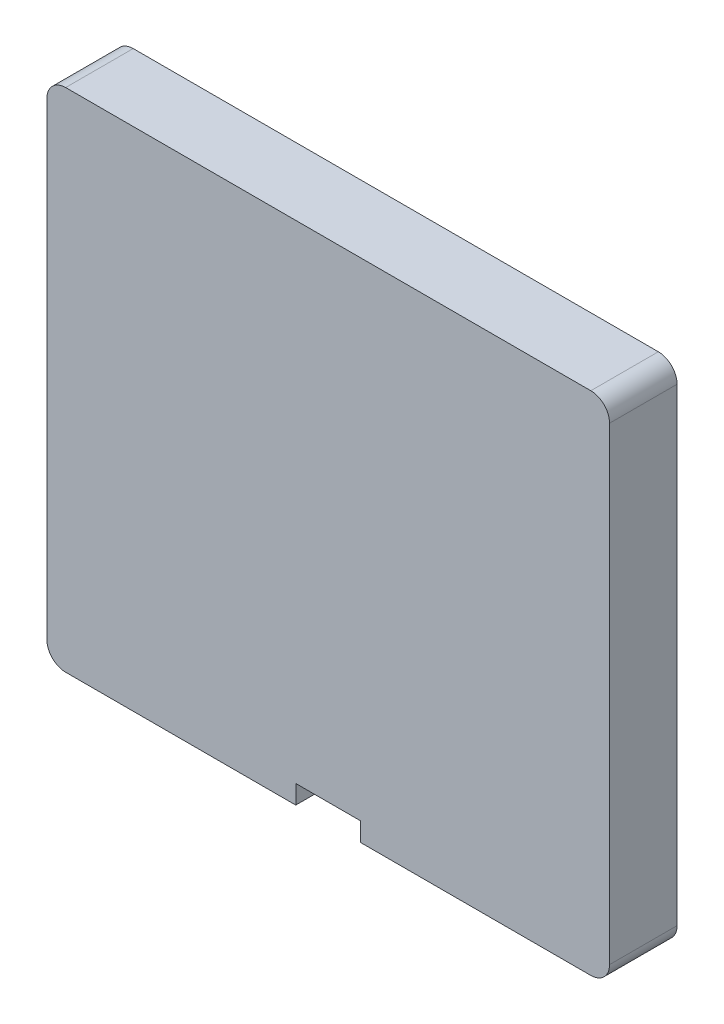
SolidWorks part; units mm, degrees
ref_plane "前视基准面" through (0, 0, 0) normal (0, 0, 1) x (1, 0, 0)
ref_plane "上视基准面" through (0, 0, 0) normal (0, 1, 0) x (1, 0, 0)
ref_plane "右视基准面" through (0, 0, 0) normal (1, 0, 0) x (0, 0, -1)
sketch "草图1" plane through (0, 0, 0) normal (0, 0, 1) x (1, 0, 0)
  line L0 (0, -62.5) -> (0, -47.6331) construction
  line L1 (-70, -67.5) -> (-8.6603, -67.5)
  line L2 (-75, -62.5) -> (-75, 62.5)
  line L3 (-70, 67.5) -> (70, 67.5)
  line L4 (75, -62.5) -> (75, 62.5)
  line L5 (-75, -67.5) -> (75, 67.5) construction
  line L6 (-75, 67.5) -> (75, -67.5) construction
  line L8 (8.6603, -67.5) -> (8.6603, -62.5)
  line L9 (8.6603, -62.5) -> (-8.6603, -62.5)
  line L11 (-8.6603, -67.5) -> (-8.6603, -62.5)
  line L13 (8.6603, -67.5) -> (70, -67.5)
  arc A0 (70, 67.5) -> (75, 62.5) centre (70, 62.5) cw
  arc A1 (70, -67.5) -> (75, -62.5) centre (70, -62.5) ccw
  arc A2 (-70, -67.5) -> (-75, -62.5) centre (-70, -62.5) cw
  arc A3 (-75, 62.5) -> (-70, 67.5) centre (-70, 62.5) cw
  point P0 (0, 0)
  point P25 (0, -62.5)
  dimension "D3" = 5
  dimension "D1" = 135
  dimension "D2" = 150
  dimension "D4" = 10
  dimension "D5" = 5
extrude "凸台-拉伸1" add sketch "草图1" along normal blind 18
